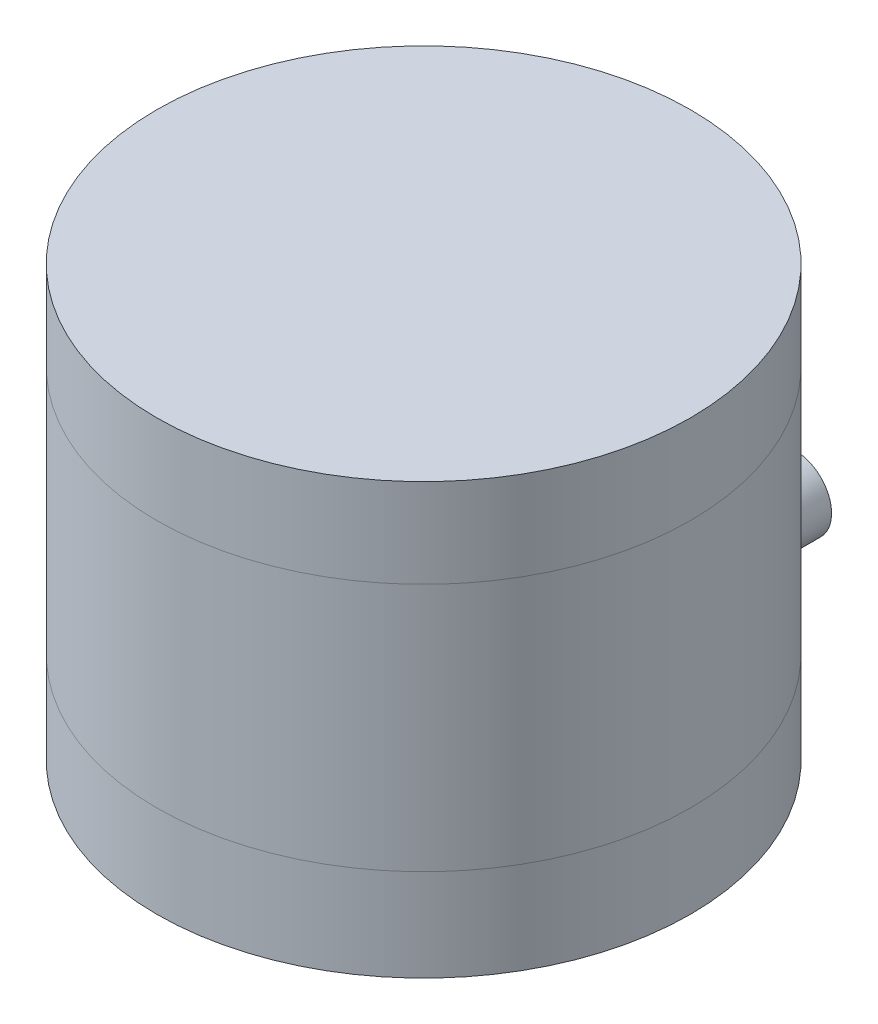
SolidWorks part; units mm, degrees
ref_plane "Front Plane" through (0, 0, 0) normal (0, 0, 1) x (1, 0, 0)
ref_plane "Top Plane" through (0, 0, 0) normal (0, 1, 0) x (1, 0, 0)
ref_plane "Right Plane" through (0, 0, 0) normal (1, 0, 0) x (0, 0, -1)
sketch "Sketch1" plane through (0, 0, 0) normal (0, 1, 0) x (1, 0, 0)
  circle A0 centre (0, 0) radius 50.4
  dimension "D1" = 100.8
extrude "Boss-Extrude1" add sketch "Sketch1" along normal blind 17.4
sketch "Sketch2" plane through (0, 17.4, 0) normal (0, 1, 0) x (1, 0, 0)
  circle A0 centre (0, 0) radius 50.4
  point P3 (0, 0)
extrude "Boss-Extrude4" add sketch "Sketch2" along normal blind 47 separate body
sketch "Sketch3" plane through (0, 64.4, 0) normal (0, 1, 0) x (1, 0, 0)
  circle A0 centre (0, 0) radius 50.4
extrude "Boss-Extrude5" add sketch "Sketch3" along normal blind 16.8 separate body
sketch "Sketch5" plane through (0, 0, 0) normal (0, -1, 0) x (1, 0, 0)
  line L0 (0, 51.9883) -> (0, -59.5503) construction
  line L1 (9.5, -50.4) -> (-9.5, -50.4) construction
  line L2 (-9.277, -54.4) -> (9.277, -54.4)
  line L3 (-11.1189, -49.1582) -> (11.1189, -49.1582)
  circle A0 centre (0, 0) radius 50.4 construction
  spline S0 degree 3 poles (-11.1189, -49.1582) (-8.7923, -50.4571) (-10.5734, -52.7611) (-9.277, -54.4) knots 0 0 0 0 1 1 1 1
  spline S1 degree 3 poles (11.1189, -49.1582) (8.7923, -50.4571) (10.5734, -52.7611) (9.277, -54.4) knots 0 0 0 0 1 1 1 1
  point P8 (0, -50.4)
  point P19 (0, -54.4)
  dimension "D1" = 4
extrude "Boss-Extrude7" add sketch "Sketch5" against normal blind 17.4 separate body
sketch "Sketch6" plane through (0, 0, -54.4) normal (0, 0, -1) x (-1, 0, 0)
  line L0 (0, 0) -> (0, 17.4) construction
  line L1 (9.277, 17.4) -> (-9.277, 17.4) construction
  line L3 (0, 17.2499) -> (-7.4044, 12.9749)
  line L4 (-7.4044, 12.9749) -> (-7.4044, 4.4251)
  line L5 (-7.4044, 4.4251) -> (0, 0.1501)
  line L6 (0, 0.1501) -> (7.4044, 4.4251)
  line L7 (7.4044, 4.4251) -> (7.4044, 12.9749)
  line L8 (7.4044, 12.9749) -> (0, 17.2499)
  circle A0 centre (0, 8.7) radius 7.4044 construction
  point P6 (0, 15.8983)
  point P14 (-7.4044, 4.4251)
extrude "Boss-Extrude8" add sketch "Sketch6" along normal blind 2.4
sketch "Sketch7" plane through (0, 0, -56.8) normal (0, 0, -1) x (-1, 0, 0)
  line L0 (0, 0.1501) -> (0, 17.2499) construction
  circle A0 centre (0, 8.7) radius 6.8403
extrude "Boss-Extrude9" add sketch "Sketch7" along normal blind 13.4
